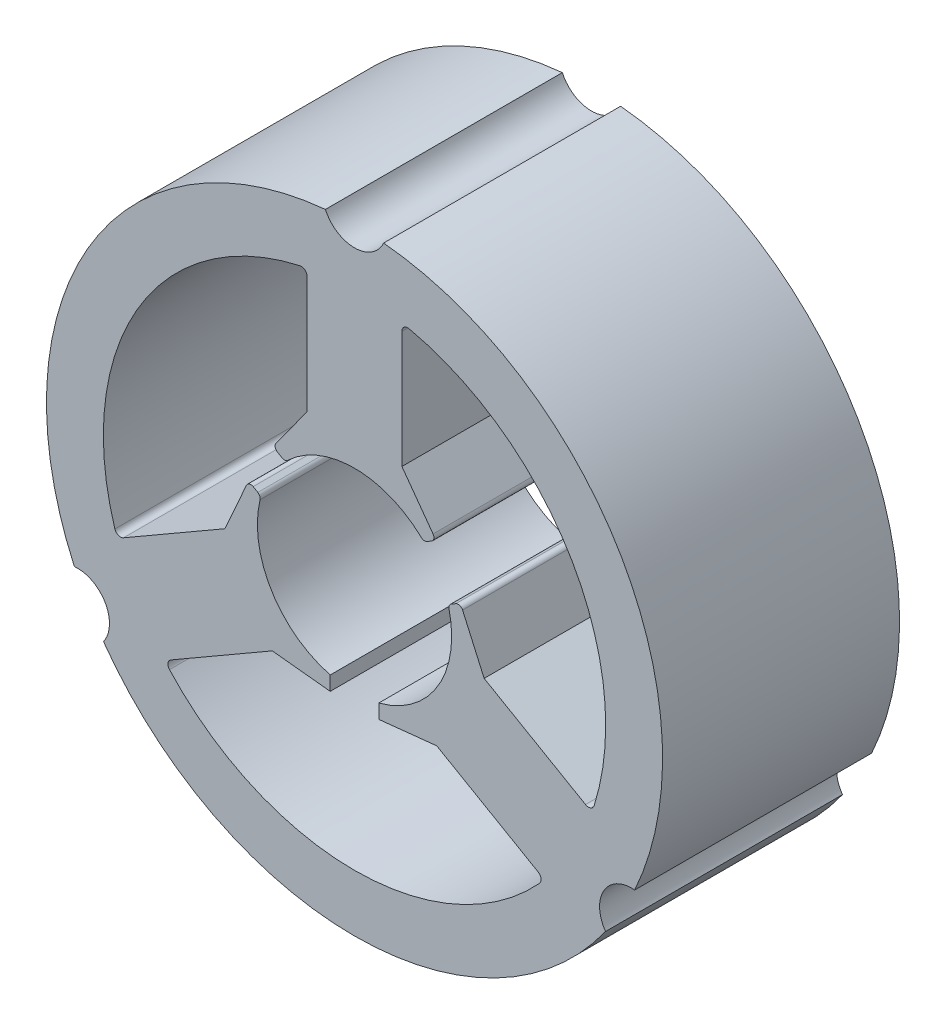
SolidWorks part; units mm, degrees
ref_plane "前视基准面" through (0, 0, 0) normal (0, 0, 1) x (1, 0, 0)
ref_plane "上视基准面" through (0, 0, 0) normal (0, 1, 0) x (1, 0, 0)
ref_plane "右视基准面" through (0, 0, 0) normal (1, 0, 0) x (0, 0, -1)
sketch "草图1" plane through (0, 0, 0) normal (0, 0, 1) x (1, 0, 0)
  line L0 (-21.4536, 0) -> (25.5305, 0) construction
  line L1 (0, 19.7631) -> (0, -19.5145) construction
  line L14 (-0.6212, 13.5) -> (0.4164, 13.5) construction
  line L15 (12.0019, -6.2121) -> (11.4831, -7.1106) construction
  line L16 (-11.3808, -7.2879) -> (-11.8995, -6.3894) construction
  line L17 (0, 0) -> (14.054, -8.1141) construction
  line L18 (0, 0) -> (-15.2933, -8.8296) construction
  circle A1 centre (0, 0) radius 4.1
  arc A7 (-1.2292, 12.9418) -> (-11.8225, -5.4064) centre (0, 0) ccw
  arc A8 (-1.2292, 12.9418) -> (1.2292, 12.9418) centre (0, 13.5) ccw
  arc A9 (11.8225, -5.4064) -> (10.5933, -7.5354) centre (11.6913, -6.75) ccw
  arc A10 (-10.5933, -7.5354) -> (-11.8225, -5.4064) centre (-11.6913, -6.75) ccw
  arc A11 (11.8225, -5.4064) -> (1.2292, 12.9418) centre (0, 0) ccw
  arc A12 (-10.5933, -7.5354) -> (10.5933, -7.5354) centre (0, 0) ccw
  point P24 (0, 0)
  point P31 (0, 0)
  dimension "D1" = 26
  dimension "D2" = 8.2
  dimension "D3" = 1.35
  dimension "D4" = 13.5
  dimension "D7" = 120
  dimension "D5" = 3
  dimension "D6" = 120
extrude "凸台-拉伸1" add sketch "草图1" along normal blind 10
sketch "草图2" plane through (0, 0, 0) normal (0, 0, 1) x (1, 0, 0)
  line L0 (-18.2914, 0) -> (18.1831, 0) construction
  line L1 (0, 18.2481) -> (0, -17.8941) construction
  line L2 (0, 0) -> (17.402, -10.0471) construction
  line L3 (-7.749, -6.7833) -> (-3.47, -4.3128)
  line L4 (-3.47, -4.3128) -> (-1.025, -4.5698)
  line L5 (0, 0) -> (-16.8155, -9.7084) construction
  line L6 (-1.025, -4.5698) -> (-1.025, -3.9698)
  line L7 (1.025, -4.5698) -> (1.025, -3.9698)
  line L8 (3.47, -4.3128) -> (1.025, -4.5698)
  line L9 (7.749, -6.7833) -> (3.47, -4.3128)
  arc A0 (-7.8082, -7.1689) -> (7.8082, -7.1689) centre (0, 0) ccw
  arc A3 (7.8082, -7.1689) -> (7.749, -6.7833) centre (7.624, -6.9998) ccw
  arc A4 (-7.8082, -7.1689) -> (-7.749, -6.7833) centre (-7.624, -6.9998) cw
  arc A7 (-1.025, -3.9698) -> (1.025, -3.9698) centre (0, 0) ccw
  point P13 (0, 0)
  point P14 (0, 0)
  point P19 (1.025, -4.2698)
  point P21 (8.015, -6.9369)
  point P24 (-8.015, -6.9369)
  dimension "D2" = 21.2
  dimension "D8" = 0.25
  dimension "D11" = 0.25
  dimension "D12" = 4.1
  dimension "D1" = 120
  dimension "D3" = 120
  dimension "D4" = 2
  dimension "D5" = 144
  dimension "D6" = 2.05
  dimension "D7" = 0.6
  dimension "D9" = 2
  dimension "D10" = 60
extrude "切除-拉伸1" cut sketch "草图2" along normal blind 10
pattern_circular "阵列(圆周)1" count 3 over 360 about axis through (0, 0, 0) along (0, 0, 1) of "切除-拉伸1"
fillet "圆角1" radius 0.2 8 edges at (-2.9255, 2.8726, 5) (-3.4451, 3.1726, 5) (4.4701, 1.3972, 5) (3.9505, 1.0972, 5) (3.4451, 3.1726, 5) (2.9255, 2.8726, 5) (-3.9505, 1.0972, 5) (-4.4701, 1.3972, 5)
